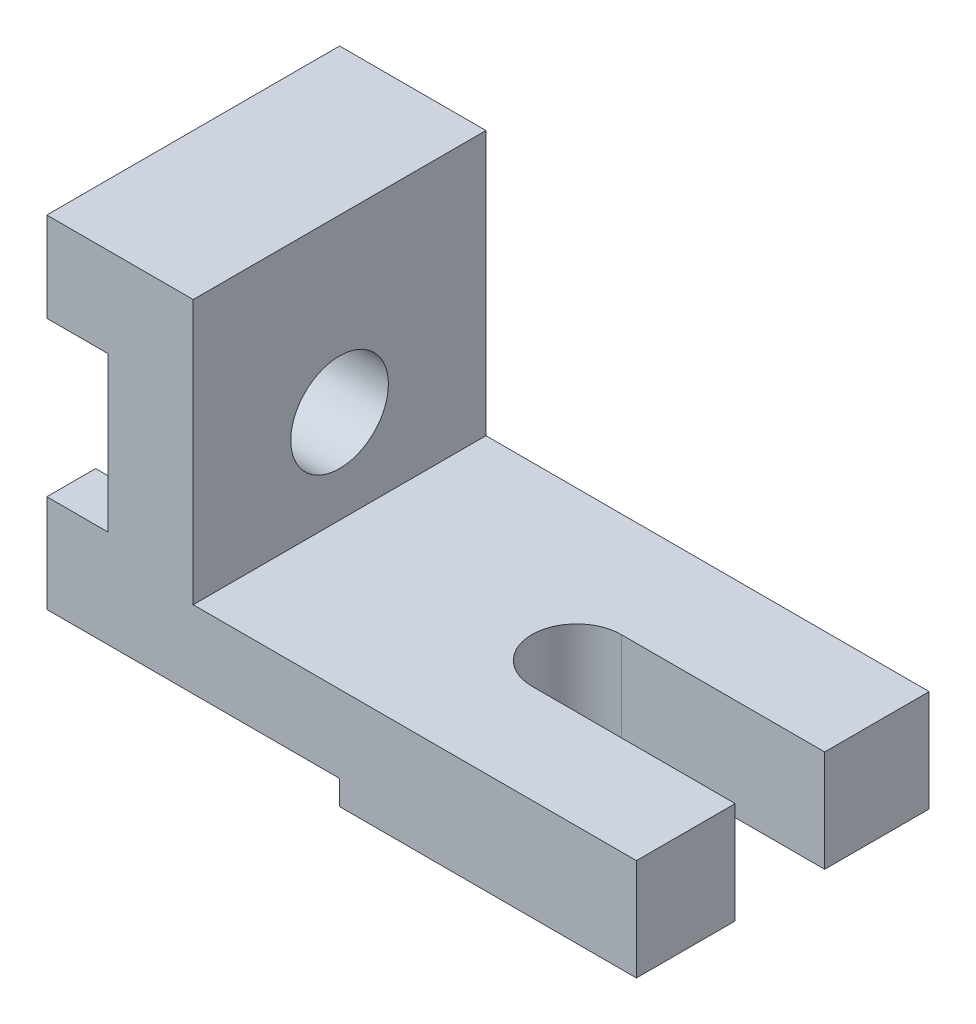
SolidWorks part; units mm, degrees
ref_plane "Front Plane" through (0, 0, 0) normal (0, 0, 1) x (1, 0, 0)
ref_plane "Top Plane" through (0, 0, 0) normal (0, 1, 0) x (1, 0, 0)
ref_plane "Right Plane" through (0, 0, 0) normal (1, 0, 0) x (0, 0, -1)
sketch "Sketch1" plane through (0, 0, 0) normal (0, 1, 0) x (1, 0, 0)
  line L1 (-72.5, 36) -> (72.5, 36)
  line L2 (-72.5, 36) -> (-72.5, -36)
  line L3 (-72.5, -36) -> (72.5, -36)
  line L4 (72.5, 36) -> (72.5, -36)
  line L5 (-72.5, 36) -> (72.5, -36) construction
  line L6 (-72.5, -36) -> (72.5, 36) construction
  point P0 (0, 0)
  dimension "D1" = 145
  dimension "D2" = 72
extrude "Boss-Extrude1" add sketch "Sketch1" along normal blind 25
sketch "Sketch2" plane through (0, 0, 36) normal (0, 0, 1) x (1, 0, 0)
  line L1 (-72.5, 0) -> (-0.5, 0)
  line L2 (-72.5, 0) -> (-72.5, 6)
  line L3 (-72.5, 6) -> (-0.5, 6)
  line L4 (-0.5, 0) -> (-0.5, 6)
  dimension "D1" = 6
  dimension "D2" = 72
extrude "Cut-Extrude1" cut sketch "Sketch2" against normal blind 50
sketch "Sketch3" plane through (0, 25, 0) normal (0, 1, 0) x (1, 0, 0)
  line L0 (72.5, -36) -> (72.5, 36) construction
  line L1 (22.5, 10.2921) -> (72.5, 10.2921)
  line L3 (22.5, -11.7079) -> (72.5, -11.7079)
  line L4 (72.5, 10.2921) -> (72.5, -11.7079)
  line L5 (22.5, -0.7079) -> (72.5, -0.7079) construction
  arc A0 (22.5, 10.2921) -> (22.5, -11.7079) centre (22.5, -0.7079) ccw
  dimension "D3" = 22
  dimension "D1" = 22
  dimension "D2" = 50
extrude "Cut-Extrude2" cut sketch "Sketch3" against normal blind 50
sketch "Sketch4" plane through (0, 0, 36) normal (0, 0, 1) x (1, 0, 0)
  line L0 (-72.5, 25) -> (-36.5, 25)
  line L1 (-72.5, 25) -> (72.5, 25) construction
  line L2 (-36.5, 25) -> (-36.5, 90)
  line L3 (-36.5, 90) -> (-72.5, 90)
  line L4 (-72.5, 90) -> (-72.5, 25)
  line L5 (-72.5, 0) -> (-0.5, 0) construction
  dimension "D1" = 36
  dimension "D2" = 90
extrude "Boss-Extrude2" add sketch "Sketch4" against normal up to surface (72 mm away) up to face at (0, 12.5, -36)
sketch "Sketch5" plane through (-72.5, 0, 0) normal (-1, 0, 0) x (0, 0, 1)
  line L0 (0, 90) -> (0, -5.7262) construction
  line L1 (-36, 90) -> (36, 90) construction
  line L2 (-36, 0) -> (-14, 0) construction
  circle A0 centre (0, 48) radius 30
  circle A1 centre (0, 48) radius 12
  dimension "D1" = 24
  dimension "D2" = 60
  dimension "D3" = 48
extrude "Cut-Extrude3" cut sketch "Sketch5" against normal blind 15 contours A0
sketch "Sketch6" plane through (0, 0, 36) normal (0, 0, 1) x (1, 0, 0)
  line L0 (-72.5, 68) -> (-57.5, 68)
  line L1 (-72.5, 90) -> (-72.5, 6) construction
  line L2 (-57.5, 68) -> (-57.5, 30)
  line L3 (-57.5, 30) -> (-72.5, 30)
  line L4 (-72.5, 30) -> (-72.5, 68)
  line L5 (-36.5, 90) -> (-72.5, 90) construction
  line L6 (-72.5, 0) -> (-0.5, 0) construction
  dimension "D1" = 15
  dimension "D2" = 22
  dimension "D3" = 30
extrude "Cut-Extrude4" cut sketch "Sketch6" against normal through all
sketch "Sketch7" plane through (-57.5, 0, 0) normal (-1, 0, 0) x (0, 0, 1)
  circle A0 centre (0, 48) radius 12
  dimension "D1" = 24
extrude "Cut-Extrude5" cut sketch "Sketch7" against normal through all
